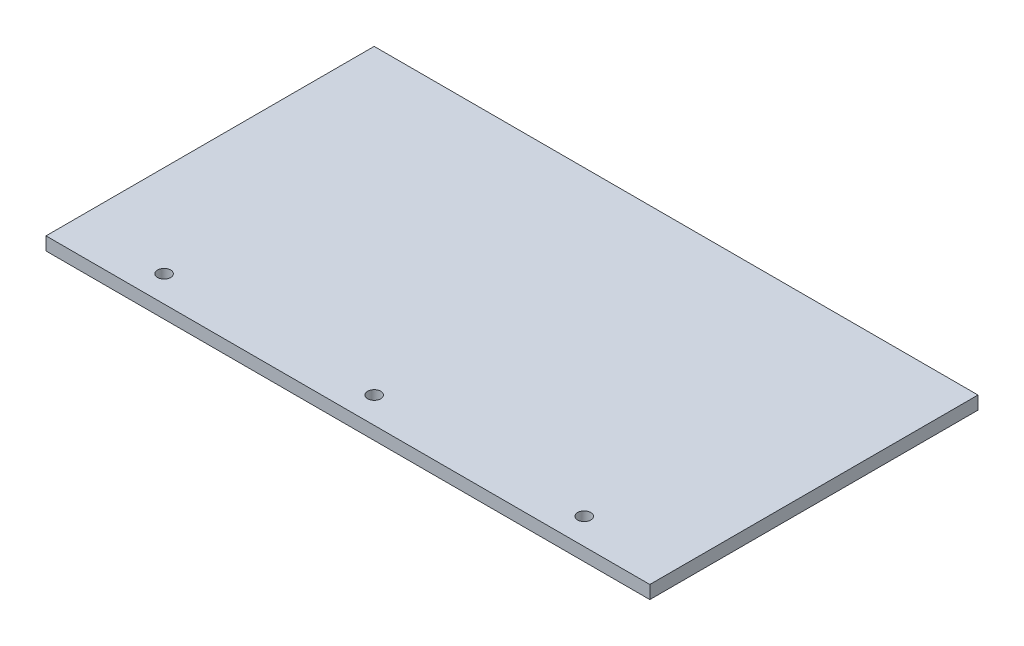
SolidWorks part; units mm, degrees
ref_plane "Front Plane" through (0, 0, 0) normal (0, 0, 1) x (1, 0, 0)
ref_plane "Top Plane" through (0, 0, 0) normal (0, 1, 0) x (1, 0, 0)
ref_plane "Right Plane" through (0, 0, 0) normal (1, 0, 0) x (0, 0, -1)
sketch "Sketch1" plane through (0, 0, 0) normal (0, 1, 0) x (1, 0, 0)
  line L1 (0, 0) -> (292.1, 0)
  line L2 (0, 0) -> (0, 158.75)
  line L3 (0, 158.75) -> (292.1, 158.75)
  line L4 (292.1, 0) -> (292.1, 158.75)
  dimension "D1" = 292.1
  dimension "D2" = 158.75
extrude "Boss-Extrude1" add sketch "Sketch1" along normal blind 6.35
sketch "Sketch2" plane through (0, 6.35, 0) normal (0, 1, 0) x (1, 0, 0)
  line L0 (0, 25.4) -> (292.1, 25.4) construction
  line L1 (0, 12.7) -> (292.1, 12.7) construction
  line L2 (146.05, 0) -> (146.05, 158.75) construction
  line L4 (0, 158.75) -> (0, 0)
  line L5 (0, 0) -> (292.1, 0)
  line L6 (292.1, 0) -> (292.1, 158.75)
  line L7 (292.1, 158.75) -> (0, 158.75)
  line L8 (0, 158.75) -> (0, 0) construction
  line L9 (0, 0) -> (292.1, 0) construction
  line L10 (292.1, 0) -> (292.1, 158.75) construction
  line L11 (292.1, 158.75) -> (0, 158.75) construction
  circle A0 centre (146.05, 12.7) radius 3.175
  circle A1 centre (247.65, 12.7) radius 3.175
  circle A2 centre (44.45, 12.7) radius 3.175
  dimension "D6" = 6.35
  dimension "D7" = 6.35
  dimension "D8" = 6.35
  dimension "D2" = 25.4
  dimension "D3" = 12.7
  dimension "D4" = 101.6
  dimension "D5" = 101.6
  dimension "D1" = 0
extrude "Cut-Extrude2" cut sketch "Sketch2" against normal blind 6.35
sketch "Sketch4" [suppressed] plane through (0, 6.35, 0) normal (0, 1, 0) x (1, 0, 0)
  line L4 (279.4, 85.09) -> (177.8, 85.09)
  line L5 (177.8, 85.09) -> (177.8, 31.75)
  line L6 (177.8, 31.75) -> (279.4, 31.75)
  line L7 (279.4, 31.75) -> (279.4, 85.09)
  line L8 (279.4, 85.09) -> (177.8, 85.09) construction
  line L9 (177.8, 85.09) -> (177.8, 31.75) construction
  line L10 (177.8, 31.75) -> (279.4, 31.75) construction
  line L11 (279.4, 31.75) -> (279.4, 85.09) construction
  line L160 (114.3, 31.75) -> (114.3, 85.09)
  line L161 (114.3, 85.09) -> (12.7, 85.09)
  line L162 (12.7, 85.09) -> (12.7, 31.75)
  line L163 (12.7, 31.75) -> (114.3, 31.75)
  line L164 (114.3, 31.75) -> (114.3, 85.09) construction
  line L165 (114.3, 85.09) -> (12.7, 85.09) construction
  line L166 (12.7, 85.09) -> (12.7, 31.75) construction
  line L167 (12.7, 31.75) -> (114.3, 31.75) construction
  circle A1 centre (182.88, 82.55) radius 1.5875
  circle A2 centre (182.88, 82.55) radius 1.5875
  circle A3 centre (189.23, 34.29) radius 1.5875
  circle A4 centre (189.23, 34.29) radius 1.5875
  circle A5 centre (265.43, 82.55) radius 1.5875
  circle A6 centre (265.43, 82.55) radius 1.5875
  circle A7 centre (264.16, 34.29) radius 1.5875
  circle A8 centre (264.16, 34.29) radius 1.5875
  circle A9 centre (264.795, 142.875) radius 1.5875
  circle A10 centre (264.795, 142.875) radius 1.5875
  circle A11 centre (264.795, 94.615) radius 1.5875
  circle A12 centre (264.795, 94.615) radius 1.5875
  circle A13 centre (198.755, 97.79) radius 1.5875
  circle A14 centre (198.755, 97.79) radius 1.5875
  circle A15 centre (198.755, 139.7) radius 1.5875
  circle A16 centre (198.755, 139.7) radius 1.5875
  circle A313 centre (102.87, 82.55) radius 1.5875
  circle A314 centre (102.87, 82.55) radius 1.5875
  circle A315 centre (109.22, 34.29) radius 1.5875
  circle A316 centre (109.22, 34.29) radius 1.5875
  circle A317 centre (26.67, 34.29) radius 1.5875
  circle A318 centre (26.67, 34.29) radius 1.5875
  circle A319 centre (27.94, 82.55) radius 1.5875
  circle A320 centre (27.94, 82.55) radius 1.5875
  circle A321 centre (93.345, 139.7) radius 1.5875
  circle A322 centre (93.345, 139.7) radius 1.5875
  circle A323 centre (93.345, 97.79) radius 1.5875
  circle A324 centre (93.345, 97.79) radius 1.5875
  circle A325 centre (27.305, 142.875) radius 1.5875
  circle A326 centre (27.305, 142.875) radius 1.5875
  circle A327 centre (27.305, 94.615) radius 1.5875
  circle A328 centre (27.305, 94.615) radius 1.5875
  dimension "D1" = 0
  dimension "D2" = 0
  dimension "D3" = 0
  dimension "D4" = 0
  dimension "D5" = 0
  dimension "D6" = 0
  dimension "D7" = 0
  dimension "D8" = 0
  dimension "D9" = 0
  dimension "D10" = 0
  dimension "D11" = 0
  dimension "D12" = 0
  dimension "D13" = 0
  dimension "D14" = 0
  dimension "D15" = 0
  dimension "D16" = 0
  dimension "D17" = 0
  dimension "D18" = 0
sketch "Sketch5" [suppressed] plane through (0, 6.35, 0) normal (0, 1, 0) x (1, 0, 0)
  line L0 (0, 0) -> (292.1, 0) construction
  line L1 (279.4, 31.75) -> (143.9, 31.75) construction
  line L2 (279.4, 31.75) -> (279.4, 75.25) construction
  line L3 (279.4, 75.25) -> (143.9, 75.25) construction
  line L4 (143.9, 31.75) -> (143.9, 75.25) construction
  line L5 (292.1, 0) -> (292.1, 158.75) construction
  circle A0 centre (279.4, 31.75) radius 1.525
  circle A1 centre (279.4, 75.25) radius 1.525
  circle A2 centre (143.9, 75.25) radius 1.525
  circle A3 centre (143.9, 31.75) radius 1.525
  dimension "D3" = 3.05
  dimension "D1" = 43.5
  dimension "D2" = 135.5
  dimension "D4" = 31.75
  dimension "D5" = 12.7
equation "\"D5@Sketch2\"=\"D4@Sketch2\""
equation "\"D7@Sketch2\"=\"D6@Sketch2\""
equation "\"D8@Sketch2\"=\"D7@Sketch2\""
equation "\"D4@Sketch5\"=1.25*25.4"
